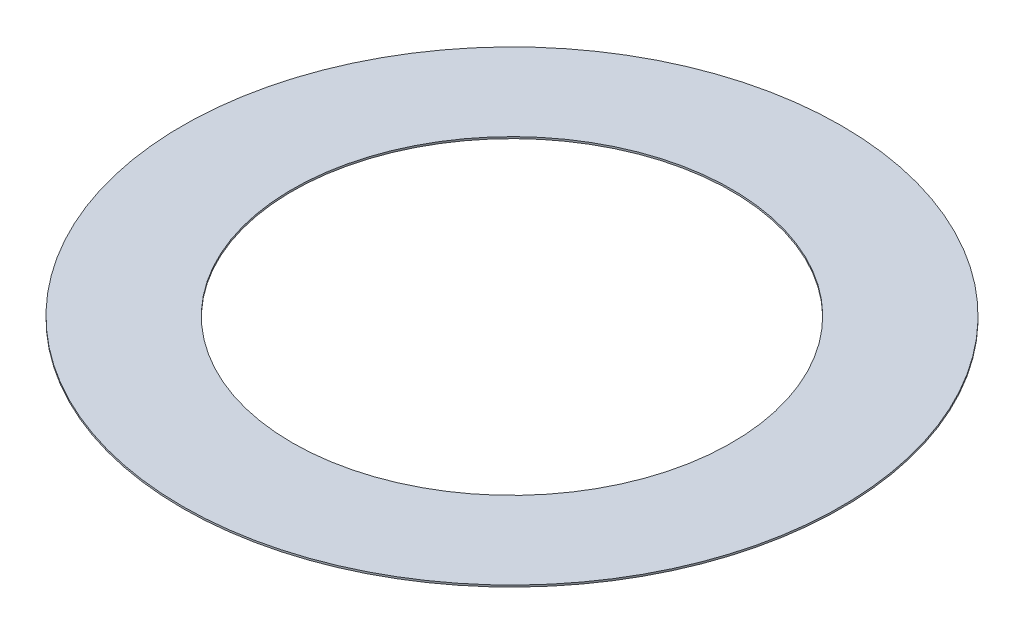
SolidWorks part; units mm, degrees
material "AISI 316 Annealed Stainless Steel Bar (SS)"
ref_plane "Front" through (0, 0, 0) normal (0, 0, 1) x (1, 0, 0)
ref_plane "Top" through (0, 0, 0) normal (0, 1, 0) x (1, 0, 0)
ref_plane "Right" through (0, 0, 0) normal (1, 0, 0) x (0, 0, -1)
sketch "Sketch1" plane through (0, 0, 0) normal (0, 1, 0) x (1, 0, 0)
  circle A0 centre (0, 0) radius 3.175
  circle A1 centre (0, 0) radius 4.7625
  dimension "D1" = 9.525
  dimension "D2" = 6.35
extrude "Boss-Extrude1" add sketch "Sketch1" along normal blind 0.0254
